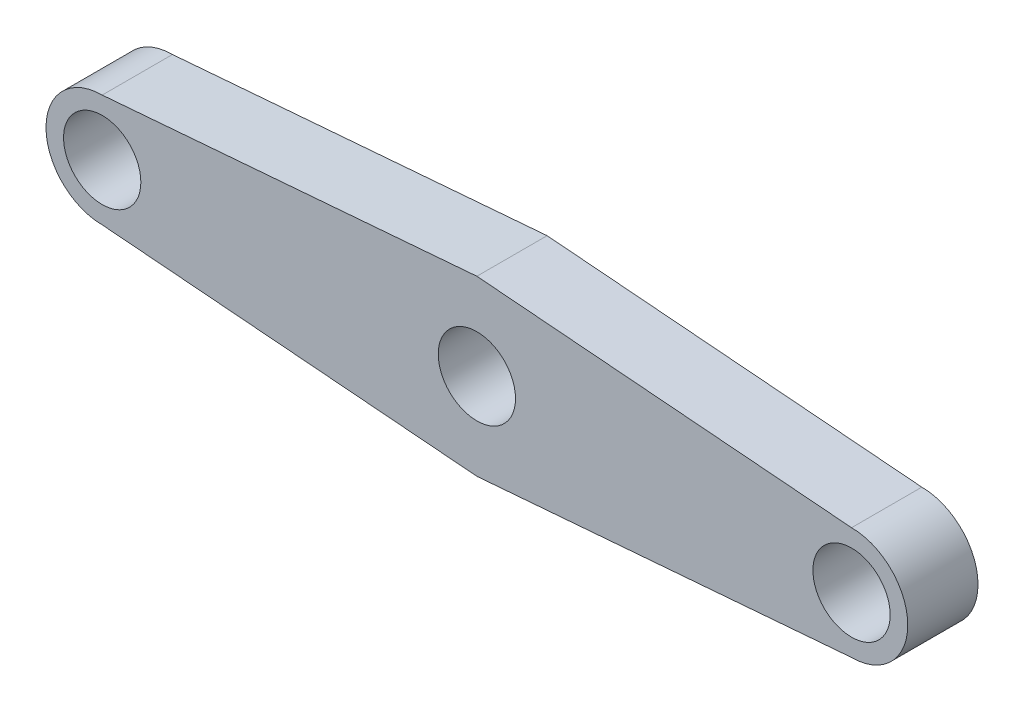
SolidWorks part; units mm, degrees
ref_plane "前视基准面" through (0, 0, 0) normal (0, 0, 1) x (1, 0, 0)
ref_plane "上视基准面" through (0, 0, 0) normal (0, 1, 0) x (1, 0, 0)
ref_plane "右视基准面" through (0, 0, 0) normal (1, 0, 0) x (0, 0, -1)
sketch "草图1" plane through (0, 0, 0) normal (0, 0, 1) x (1, 0, 0)
  line L0 (-1000, 0) -> (49000, 0) construction
  line L1 (0, -1000) -> (0, 49000) construction
  line L2 (-16, 2.4) -> (0, 3.7)
  line L3 (-16, -2.4) -> (0, -3.7)
  line L4 (16, -2.4) -> (0, -3.7)
  line L5 (16, 2.4) -> (0, 3.7)
  circle A0 centre (0, 0) radius 1.65
  circle A1 centre (0, 0) radius 3.7
  circle A2 centre (-16, 0) radius 2.4
  circle A3 centre (16, 0) radius 2.4
  circle A4 centre (-16, 0) radius 1.65
  circle A5 centre (16, 0) radius 1.65
  dimension "D1" = 3.3
  dimension "D2" = 7.4
  dimension "D3" = 4.8
  dimension "D4" = 16
  dimension "D5" = 3.3
  dimension "D6" = 3.3
extrude "凸台-拉伸1" add sketch "草图1" along normal blind 3 contours A2 L3 A1 L2 | L2 A1 L3 L4 L5 A0 | L4 A3 L5 A1 | A3 A5 | A4
